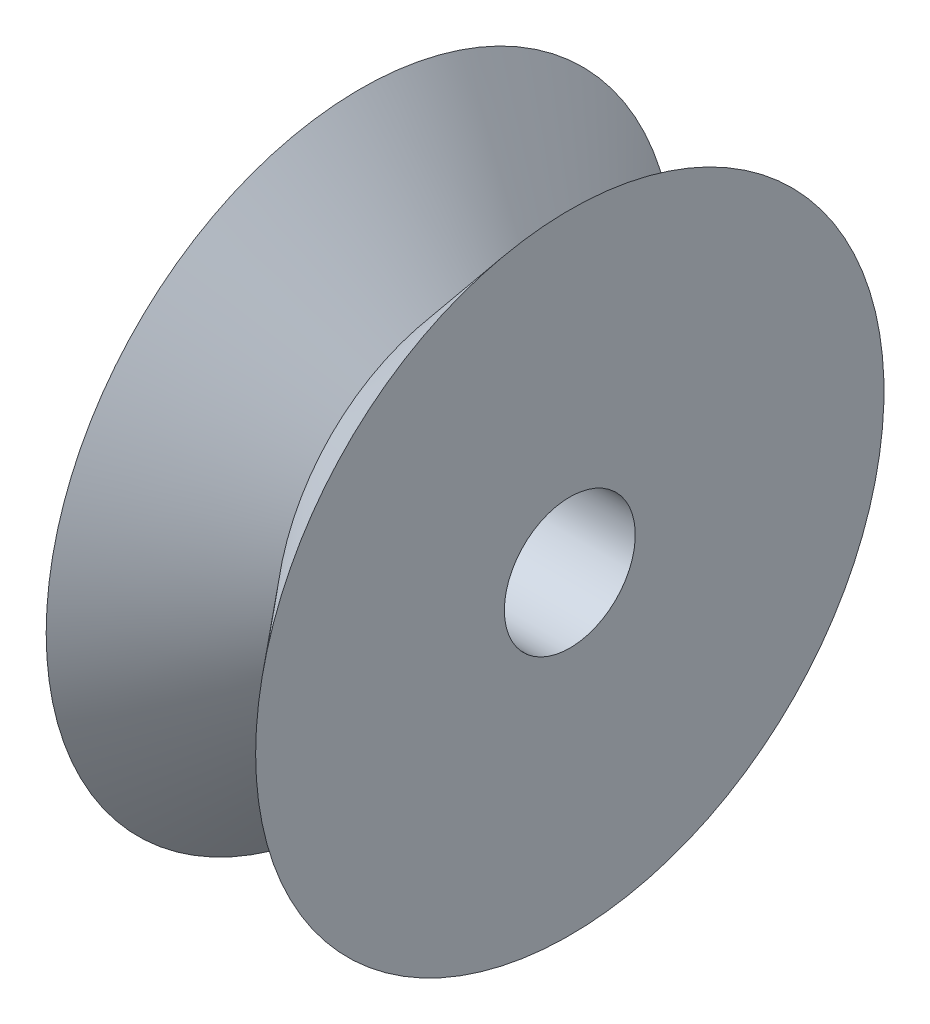
SolidWorks part; units mm, degrees
ref_plane "Front Plane" through (0, 0, 0) normal (0, 0, 1) x (1, 0, 0)
ref_plane "Top Plane" through (0, 0, 0) normal (0, 1, 0) x (1, 0, 0)
ref_plane "Right Plane" through (0, 0, 0) normal (1, 0, 0) x (0, 0, -1)
sketch "Sketch1" plane through (0, 0, 0) normal (0, 1, 0) x (1, 0, 0)
  line L0 (0, 16.35) -> (0, -18.9631) construction
  line L1 (-23.801, 0) -> (22.1766, 0) construction
  line L2 (4, 0) -> (-4, 0)
  line L3 (-4, 0) -> (-4, 12)
  line L4 (-4, 12) -> (0, 7.233)
  line L5 (4, 0) -> (4, 12)
  line L6 (4, 12) -> (0, 7.233)
  point P11 (0, 0)
  dimension "D1" = 4
  dimension "D2" = 12
  dimension "D3" = 40
revolve "Revolve1" add sketch "Sketch1" angle 360 about L1
sketch "Sketch2" plane through (-4, 0, 0) normal (-1, 0, 0) x (0, 0, 1)
  circle A0 centre (0, 0) radius 2.5
  dimension "D1" = 5
extrude "Cut-Extrude1" cut sketch "Sketch2" against normal blind 10
